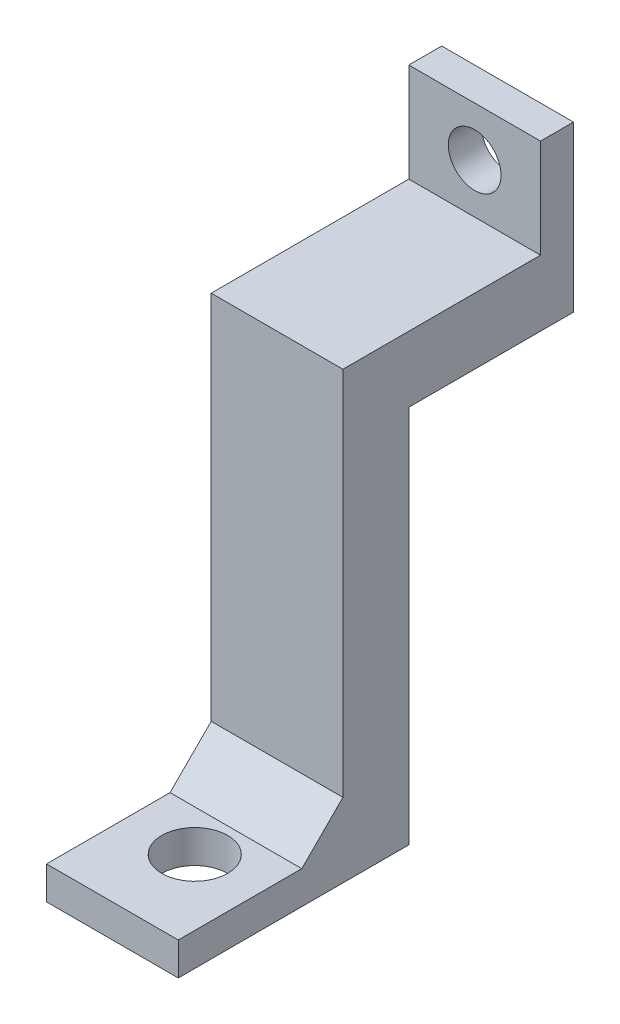
SolidWorks part; units mm, degrees
ref_plane "Front Plane" through (0, 0, 0) normal (0, 0, 1) x (1, 0, 0)
ref_plane "Top Plane" through (0, 0, 0) normal (0, 1, 0) x (1, 0, 0)
ref_plane "Right Plane" through (0, 0, 0) normal (1, 0, 0) x (0, 0, -1)
sketch "Sketch1" plane through (0, 0, 0) normal (1, 0, 0) x (0, 0, -1)
  line L2 (70.2233, 25.0177) -> (82.2233, 25.0177)
  line L3 (82.2233, 25.0177) -> (82.2233, 31.0177)
  line L4 (60.2233, 0) -> (60.2233, -2)
  line L5 (60.2233, -2) -> (70.2233, -2)
  line L6 (70.2233, -2) -> (74.2233, -2)
  line L7 (74.2233, -2) -> (74.2233, 21.0177)
  line L8 (74.2233, 21.0177) -> (84.2233, 21.0177)
  line L9 (84.2233, 21.0177) -> (84.2233, 31.0177)
  line L10 (84.2233, 31.0177) -> (82.2233, 31.0177)
  line L11 (60.2233, 0) -> (67.7233, 0)
  line L12 (67.7233, 0) -> (70.2233, 2.5)
  line L13 (70.2233, 2.5) -> (70.2233, 25.0177)
  dimension "D1" = 2
  dimension "D2" = 14
  dimension "D3" = 12
  dimension "D4" = 6
  dimension "D5" = 4
  dimension "D6" = 2
  dimension "D7" = 7.5
  dimension "D8" = 2.5
  dimension "D9" = 4
extrude "Boss-Extrude1" add sketch "Sketch1" along normal blind 8
sketch "Sketch3" plane through (0, 0, -82.2233) normal (0, 0, 1) x (1, 0, 0)
  line L0 (8, 31.0177) -> (0, 31.0177) construction
  line L1 (8, 31.0177) -> (8, 25.0177) construction
  circle A0 centre (4, 28.0177) radius 1.6
  dimension "D3" = 3.2
  dimension "D1" = 3
  dimension "D2" = 4
extrude "Cut-Extrude1" cut sketch "Sketch3" against normal blind 10
sketch "Sketch4" plane through (0, 0, 0) normal (0, 1, 0) x (1, 0, 0)
  line L0 (0, 67.7233) -> (0, 60.2233) construction
  line L1 (8, 60.2233) -> (0, 60.2233) construction
  circle A0 centre (4, 65.2233) radius 2
  dimension "D1" = 4
  dimension "D2" = 4
  dimension "D3" = 5
extrude "Cut-Extrude2" cut sketch "Sketch4" against normal blind 10
